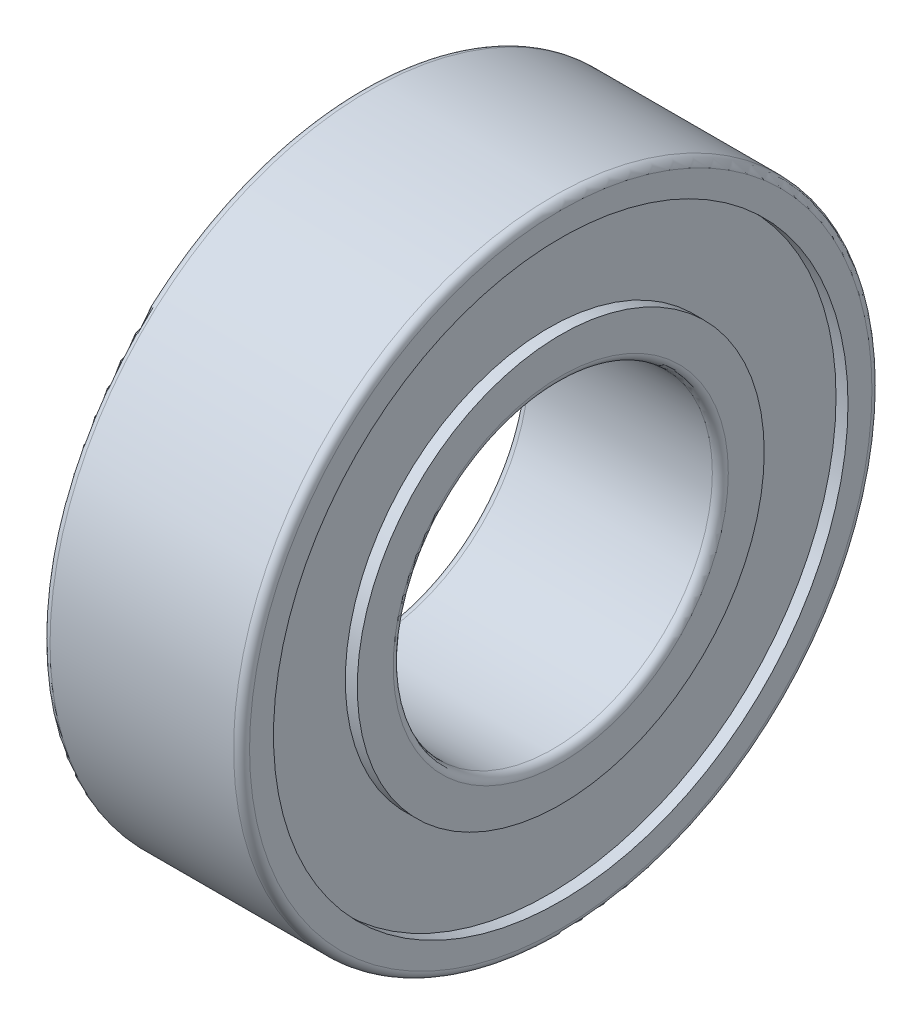
SolidWorks part; units mm, degrees
material "Plain Carbon Steel"
ref_plane "Front Plane" through (0, 0, 0) normal (0, 0, 1) x (1, 0, 0)
ref_plane "Top Plane" through (0, 0, 0) normal (0, 1, 0) x (1, 0, 0)
ref_plane "Right Plane" through (0, 0, 0) normal (1, 0, 0) x (0, 0, -1)
sketch "Sketch1" plane through (0, 0, 0) normal (0, 0, 1) x (1, 0, 0)
  line L0 (2.5, 4) -> (-2.5, 4)
  line L1 (-2.5, 4) -> (-2.5, 5.1)
  line L2 (-2.5, 5.1) -> (-2.2, 5.1)
  line L3 (-2.2, 5.1) -> (-2.2, 7.2)
  line L4 (-2.2, 7.2) -> (-2.5, 7.2)
  line L5 (-2.5, 7.2) -> (-2.5, 8)
  line L6 (-2.5, 8) -> (2.5, 8)
  line L7 (0, 8) -> (0, 4) construction
  line L8 (2.5, 7.2) -> (2.5, 8)
  line L9 (2.2, 7.2) -> (2.5, 7.2)
  line L10 (2.2, 5.1) -> (2.2, 7.2)
  line L11 (2.5, 5.1) -> (2.2, 5.1)
  line L12 (2.5, 4) -> (2.5, 5.1)
  line L13 (0, 0) -> (-4.3663, 0) construction
  dimension "D1" = 8
  dimension "D2" = 16
  dimension "D3" = 5
  dimension "D4" = 10.2
  dimension "D5" = 2.1
  dimension "D6" = 0.3
revolve "Revolve1" add sketch "Sketch1" angle 360 about L13
fillet "Fillet1" radius 0.2 4 edges at (-2.5, 0, -8) (2.5, 0, -8) (-2.5, 0, -4) (2.5, 0, -4)
